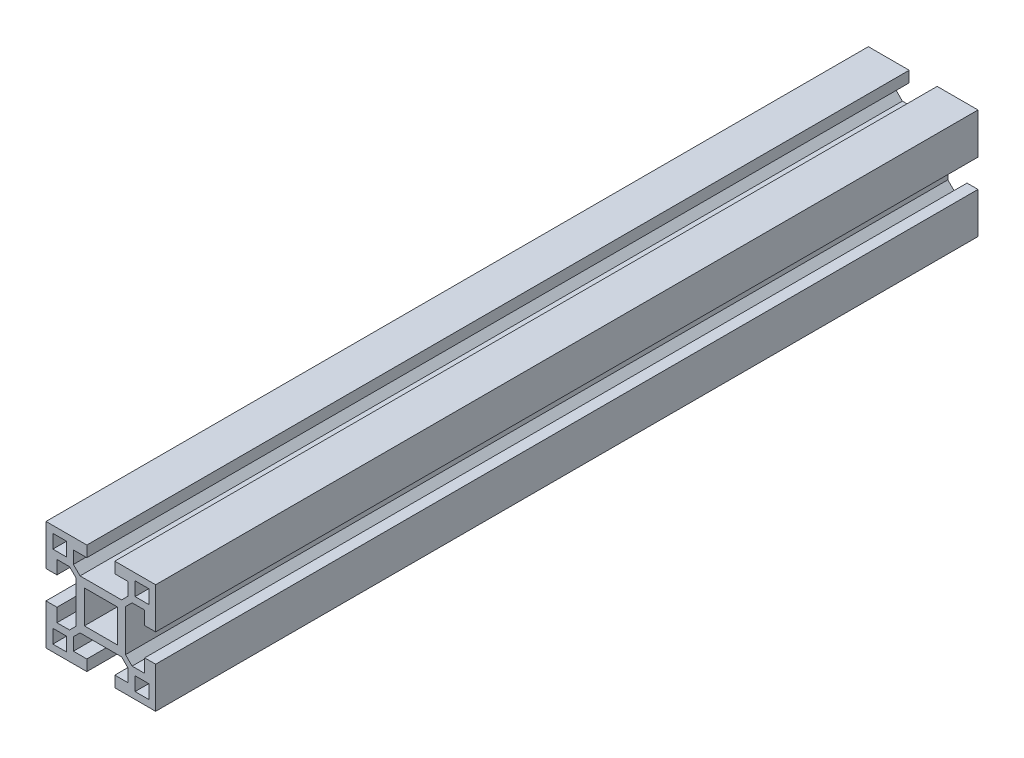
SolidWorks part; units mm, degrees
ref_plane "Plan de face" through (0, 0, 0) normal (0, 0, 1) x (1, 0, 0)
ref_plane "Plan de dessus" through (0, 0, 0) normal (0, 1, 0) x (1, 0, 0)
ref_plane "Plan de droite" through (0, 0, 0) normal (1, 0, 0) x (0, 0, -1)
sketch "Esquisse1" plane through (0, 0, 0) normal (0, 0, 1) x (1, 0, 0)
  line L0 (0, 77.7519) -> (0, -23.3251) construction
  line L1 (17.5, 17.5) -> (12.5, 17.5)
  line L2 (0, 9) -> (7.5858, 9)
  line L3 (0, 6) -> (6, 6)
  line L4 (0, 0) -> (41.9496, 41.9496) construction
  line L5 (7.5858, 9) -> (10, 11.4142)
  line L6 (10, 16) -> (5.1, 16)
  line L7 (5.1, 20) -> (5.1, 16)
  line L8 (12.5, 17.5) -> (12.5, 12.5)
  line L9 (5.1, 20) -> (20, 20)
  line L10 (15, 17.5) -> (15, 15) construction
  line L11 (10, 16) -> (10, 11.4142)
  line L12 (17.5, 15) -> (15, 15) construction
  line L13 (16, 10) -> (11.4142, 10)
  line L14 (20, 5.1) -> (20, 20)
  line L15 (17.5, 12.5) -> (12.5, 12.5)
  line L16 (20, 5.1) -> (16, 5.1)
  line L17 (16, 10) -> (16, 5.1)
  line L18 (9, 7.5858) -> (11.4142, 10)
  line L19 (6, 0) -> (6, 6)
  line L20 (9, 0) -> (9, 7.5858)
  line L21 (17.5, 17.5) -> (17.5, 12.5)
  line L22 (0, -6) -> (6, -6)
  line L23 (0, -9) -> (7.5858, -9)
  line L24 (7.5858, -9) -> (10, -11.4142)
  line L25 (6, 0) -> (6, -6)
  line L26 (9, 0) -> (9, -7.5858)
  line L27 (9, -7.5858) -> (11.4142, -10)
  line L28 (16, -10) -> (11.4142, -10)
  line L29 (16, -10) -> (16, -5.1)
  line L30 (20, -5.1) -> (16, -5.1)
  line L31 (20, -5.1) -> (20, -20)
  line L32 (17.5, -12.5) -> (12.5, -12.5)
  line L33 (17.5, -17.5) -> (17.5, -12.5)
  line L34 (17.5, -17.5) -> (12.5, -17.5)
  line L35 (10, -16) -> (10, -11.4142)
  line L36 (10, -16) -> (5.1, -16)
  line L37 (5.1, -20) -> (5.1, -16)
  line L38 (5.1, -20) -> (20, -20)
  line L39 (12.5, -17.5) -> (12.5, -12.5)
  line L40 (-6, 0) -> (-6, -6)
  line L41 (-9, 0) -> (-9, -7.5858)
  line L42 (-9, -7.5858) -> (-11.4142, -10)
  line L43 (0, -6) -> (-6, -6)
  line L44 (0, -9) -> (-7.5858, -9)
  line L45 (-7.5858, -9) -> (-10, -11.4142)
  line L46 (-10, -16) -> (-10, -11.4142)
  line L47 (-10, -16) -> (-5.1, -16)
  line L48 (-5.1, -20) -> (-5.1, -16)
  line L49 (-5.1, -20) -> (-20, -20)
  line L50 (-12.5, -17.5) -> (-12.5, -12.5)
  line L51 (-17.5, -17.5) -> (-12.5, -17.5)
  line L52 (-17.5, -17.5) -> (-17.5, -12.5)
  line L53 (-16, -10) -> (-11.4142, -10)
  line L54 (-16, -10) -> (-16, -5.1)
  line L55 (-20, -5.1) -> (-16, -5.1)
  line L56 (-20, -5.1) -> (-20, -20)
  line L57 (-17.5, -12.5) -> (-12.5, -12.5)
  line L58 (0, 6) -> (-6, 6)
  line L59 (0, 9) -> (-7.5858, 9)
  line L60 (-7.5858, 9) -> (-10, 11.4142)
  line L61 (-6, 0) -> (-6, 6)
  line L62 (-9, 0) -> (-9, 7.5858)
  line L63 (-9, 7.5858) -> (-11.4142, 10)
  line L64 (-16, 10) -> (-11.4142, 10)
  line L65 (-16, 10) -> (-16, 5.1)
  line L66 (-20, 5.1) -> (-16, 5.1)
  line L67 (-20, 5.1) -> (-20, 20)
  line L68 (-17.5, 12.5) -> (-12.5, 12.5)
  line L69 (-17.5, 17.5) -> (-17.5, 12.5)
  line L70 (-17.5, 17.5) -> (-12.5, 17.5)
  line L71 (-10, 16) -> (-10, 11.4142)
  line L72 (-10, 16) -> (-5.1, 16)
  line L73 (-5.1, 20) -> (-5.1, 16)
  line L74 (-5.1, 20) -> (-20, 20)
  line L75 (-12.5, 17.5) -> (-12.5, 12.5)
  point P0 (0, 0)
  point P6 (0, 0)
  point P93 (0, 0)
  dimension "D1" = 45
  dimension "D2" = 20
  dimension "D3" = 5.1
  dimension "D4" = 11
  dimension "D5" = 4
  dimension "D6" = 1
  dimension "D7" = 3
  dimension "D8" = 5
  dimension "D9" = 15
  dimension "D10" = 2.5
  dimension "D11" = 4
extrude "Boss.-Extru.1" add sketch "Esquisse1" along normal blind 300 contours L73 L74 L67 L66 L65 L64 L63 L62 L41 L42 L53 L54 L55 L56 L49 L48 L47 L46 L45 L44 L23 L24 L35 L36 L37 L38 L31 L30 L29 L28 L27 L26 L20 L18 L13 L17 L16 L14 L9 L7 L6 L11 L5 L2 L59 L60 L71 L72 L40 L61
